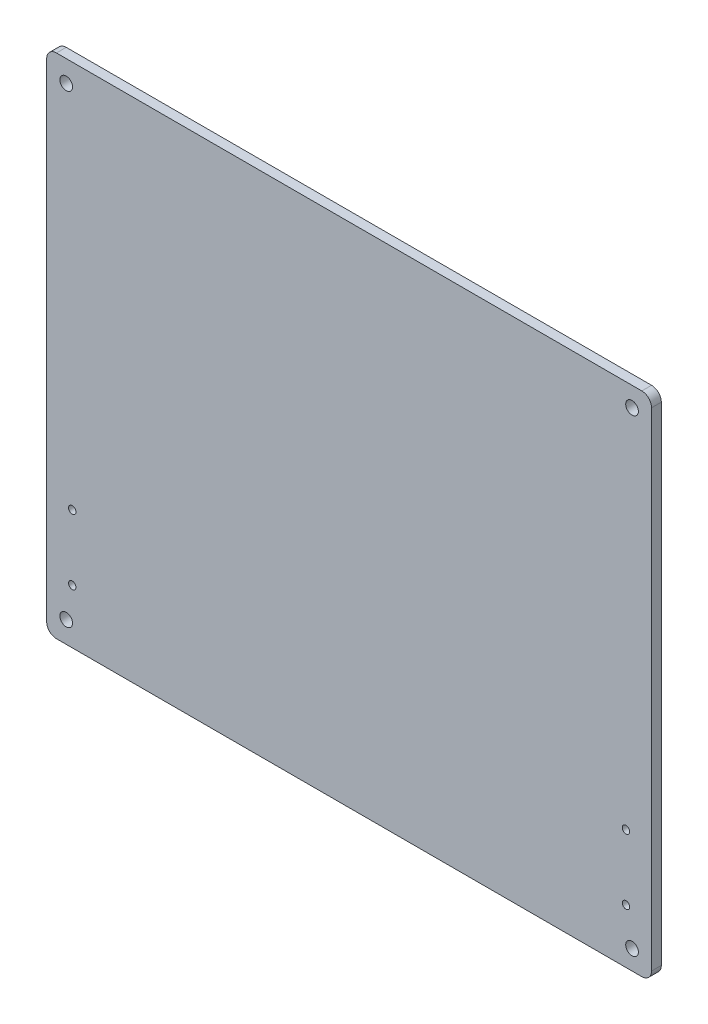
SolidWorks part; units mm, degrees
ref_plane "Front Plane" through (0, 0, 0) normal (0, 0, 1) x (1, 0, 0)
ref_plane "Top Plane" through (0, 0, 0) normal (0, 1, 0) x (1, 0, 0)
ref_plane "Right Plane" through (0, 0, 0) normal (1, 0, 0) x (0, 0, -1)
sketch "Sketch1" plane through (0, 0, 0) normal (0, 0, 1) x (1, 0, 0)
  line L0 (-145, -10) -> (-145, 14.3623) construction
  line L1 (-295, -10) -> (5, -10)
  line L2 (-300, -5) -> (-300, 245)
  line L3 (-295, 250) -> (5, 250)
  line L4 (10, -5) -> (10, 245)
  circle A0 centre (0, 0) radius 3.25
  circle A1 centre (0, 240) radius 3.25
  circle A2 centre (-290, 239) radius 3.25
  circle A3 centre (-290, 1) radius 3.25
  circle A4 centre (-286.9, 51.2174) radius 1.9
  circle A5 centre (-286.9, 17.7826) radius 1.9
  circle A6 centre (-3.1, 17.7826) radius 1.9
  circle A7 centre (-3.1, 51.2174) radius 1.9
  arc A8 (-295, -10) -> (-300, -5) centre (-295, -5) cw
  arc A9 (5, -10) -> (10, -5) centre (5, -5) ccw
  arc A10 (5, 250) -> (10, 245) centre (5, 245) cw
  arc A11 (-300, 245) -> (-295, 250) centre (-295, 245) cw
  dimension "D1" = 5
extrude "Boss-Extrude1" add sketch "Sketch1" along normal blind 5
